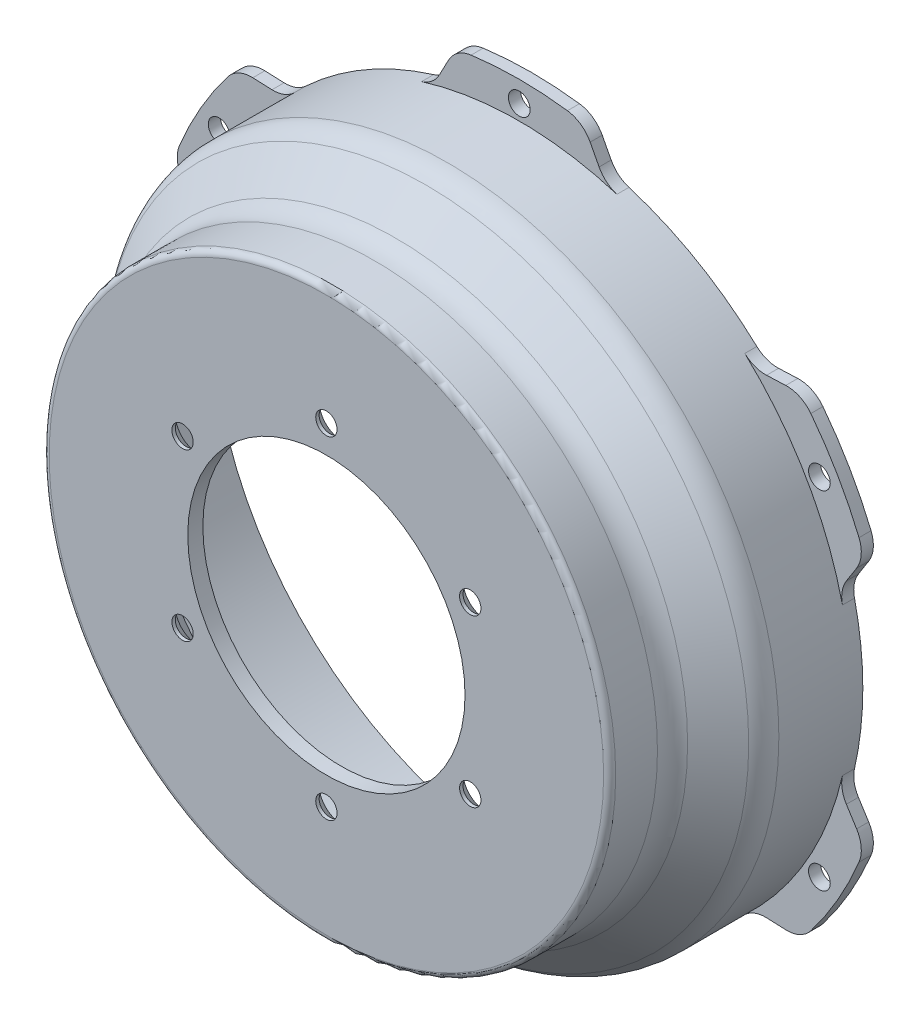
SolidWorks part; units mm, degrees
ref_plane "Front Plane" through (0, 0, 0) normal (0, 0, 1) x (1, 0, 0)
ref_plane "Top Plane" through (0, 0, 0) normal (0, 1, 0) x (1, 0, 0)
ref_plane "Right Plane" through (0, 0, 0) normal (1, 0, 0) x (0, 0, -1)
sketch "Sketch3" plane through (0, 0, 0) normal (1, 0, 0) x (0, 0, -1)
  line L0 (0, 29.21) -> (0, 58.42)
  line L4 (8.4455, 57.15) -> (8.4455, 54.61)
  line L5 (8.4455, 54.61) -> (4.445, 54.61)
  line L6 (3.175, 53.34) -> (3.175, 29.21)
  line L7 (3.175, 29.21) -> (0, 29.21)
  line L8 (0, 0) -> (50000, 0) construction
  line L9 (8.4455, 57.15) -> (14.0335, 57.15)
  line L14 (43.18, 67.31) -> (43.18, 77.47)
  line L15 (14.0335, 57.15) -> (24.1935, 67.31)
  line L16 (24.1935, 67.31) -> (43.18, 67.31)
  line L17 (40.64, 69.85) -> (25.4903, 69.85)
  line L18 (21.0001, 67.9901) -> (14.5599, 61.5499)
  line L19 (10.0697, 59.69) -> (1.27, 59.69)
  line L21 (40.64, 69.85) -> (40.64, 77.47)
  line L22 (40.64, 77.47) -> (43.18, 77.47)
  arc A0 (3.175, 53.34) -> (4.445, 54.61) centre (4.445, 53.34) cw
  arc A5 (0, 58.42) -> (1.27, 59.69) centre (1.27, 58.42) cw
  arc A6 (25.4903, 69.85) -> (21.0001, 67.9901) centre (25.4903, 63.5) ccw
  arc A7 (14.5599, 61.5499) -> (10.0697, 59.69) centre (10.0697, 66.04) cw
  point P32 (12.7, 59.69)
  dimension "D7" = 3.175
  dimension "D10" = 1.27
  dimension "D11" = 12.7
  dimension "D14" = 67.31
  dimension "D4" = 14.0335
  dimension "D2" = 6.35
  dimension "D3" = 29.21
  dimension "D5" = 8.4455
  dimension "D6" = 54.61
  dimension "D8" = 57.15
  dimension "D9" = 59.69
  dimension "D12" = 43.18
  dimension "D13" = 69.85
  dimension "D15" = 45
  dimension "D16" = 40.64
  dimension "D17" = 77.47
revolve "Revolve1" add sketch "Sketch3" angle 360 about L8
sketch "Sketch6" plane through (0, 0, -3.175) normal (0, 0, -1) x (-1, 0, 0)
  point P0 (0, 35)
  dimension "D1" = 35
hole_wizard "CSK for M4 Countersunk Flat Head Screw2" positions "Sketch6" profile "Sketch7" countersink size "M4" standard "ISO"
sketch "Sketch7" plane through (0, 35, -3.175) normal (1, 0, 0) x (0, 1, 0)
  line L0 (0, 0) -> (0, 4.5269)
  line L1 (0, 4.5269) -> (2.25, 3.175)
  line L2 (2.25, 3.175) -> (2.25, 2.45)
  line L3 (2.25, 2.45) -> (4.7, 0)
  line L5 (4.7, 0) -> (0, 0)
  line L6 (-2.25, 2.45) -> (-4.7, 0) construction
  line L10 (0, 4.5269) -> (-2.25, 3.175) construction
  line L11 (0, -6.35) -> (0, 107.95) construction
  dimension "Hole Dia." = 4.5
  dimension "Hole Depth" = 3.175
  dimension "Near C'Sink Dia." = 9.4
  dimension "Near C'Sink Angle" = 90
  dimension "Drill Angle" = 118
pattern_circular "CirPattern2" count 6 over 360 about axis through (0, 0, 0) along (0, 0, 1) of "CSK for M4 Countersunk Flat Head Screw2"
sketch "Sketch8" plane through (0, 0, -40.64) normal (0, 0, 1) x (1, 0, 0)
  line L0 (0, 0) -> (0, 77.47) construction
  line L1 (13.4525, 76.2931) -> (0, 0) construction
  line L2 (18.0785, 67.4699) -> (0, 0) construction
  line L3 (14.9401, 73.4558) -> (16.8195, 69.8713)
  line L4 (0, 0) -> (34.925, 60.4919) construction
  line L5 (-14.9401, 73.4558) -> (-16.8195, 69.8713)
  line L6 (56.1445, 49.6664) -> (52.1005, 49.5017)
  line L7 (71.0846, 23.7894) -> (68.92, 20.3695)
  line L8 (71.0846, -23.7894) -> (68.92, -20.3695)
  line L9 (56.1445, -49.6664) -> (52.1005, -49.5017)
  line L10 (14.9401, -73.4558) -> (16.8195, -69.8713)
  line L11 (-14.9401, -73.4558) -> (-16.8195, -69.8713)
  line L12 (-56.1445, -49.6664) -> (-52.1005, -49.5017)
  line L13 (-71.0846, -23.7894) -> (-68.92, -20.3695)
  line L14 (-71.0846, 23.7894) -> (-68.92, 20.3695)
  line L15 (-56.1445, 49.6664) -> (-52.1005, 49.5017)
  circle A0 centre (0, 0) radius 77.47 construction
  circle A1 centre (0, 0) radius 69.85 construction
  circle A2 centre (0, 0) radius 69.85 construction
  circle A3 centre (0, 0) radius 77.47
  arc A4 (-10.148, 76.8025) -> (10.148, 76.8025) centre (0, 0) cw
  arc A5 (20.5731, 66.7516) -> (34.925, 60.4919) centre (0, 0) cw
  arc A6 (10.148, 76.8025) -> (14.9401, 73.4558) centre (9.3162, 70.5072) cw
  arc A7 (-20.5731, 66.7516) -> (-34.925, 60.4919) centre (0, 0) ccw
  arc A8 (-10.148, 76.8025) -> (-14.9401, 73.4558) centre (-9.3162, 70.5072) ccw
  arc A9 (47.522, 51.1926) -> (34.925, 60.4919) centre (0, 0) ccw
  arc A10 (61.4389, 47.1897) -> (56.1445, 49.6664) centre (56.4029, 43.3217) ccw
  arc A11 (61.4389, 47.1897) -> (71.5869, 29.6128) centre (0, 0) cw
  arc A12 (71.5869, 29.6128) -> (71.0846, 23.7894) centre (65.7191, 27.1855) cw
  arc A13 (68.0951, 15.559) -> (69.85, 0) centre (0, 0) cw
  arc A14 (68.0951, -15.559) -> (69.85, 0) centre (0, 0) ccw
  arc A15 (71.5869, -29.6128) -> (71.0846, -23.7894) centre (65.7191, -27.1855) ccw
  arc A16 (71.5869, -29.6128) -> (61.4389, -47.1897) centre (0, 0) cw
  arc A17 (61.4389, -47.1897) -> (56.1445, -49.6664) centre (56.4029, -43.3217) cw
  arc A18 (47.522, -51.1926) -> (34.925, -60.4919) centre (0, 0) cw
  arc A19 (20.5731, -66.7516) -> (34.925, -60.4919) centre (0, 0) ccw
  arc A20 (10.148, -76.8025) -> (14.9401, -73.4558) centre (9.3162, -70.5072) ccw
  arc A21 (10.148, -76.8025) -> (-10.148, -76.8025) centre (0, 0) cw
  arc A22 (-10.148, -76.8025) -> (-14.9401, -73.4558) centre (-9.3162, -70.5072) cw
  arc A23 (-20.5731, -66.7516) -> (-34.925, -60.4919) centre (0, 0) cw
  arc A24 (-47.522, -51.1926) -> (-34.925, -60.4919) centre (0, 0) ccw
  arc A25 (-61.4389, -47.1897) -> (-56.1445, -49.6664) centre (-56.4029, -43.3217) ccw
  arc A26 (-61.4389, -47.1897) -> (-71.5869, -29.6128) centre (0, 0) cw
  arc A27 (-71.5869, -29.6128) -> (-71.0846, -23.7894) centre (-65.7191, -27.1855) cw
  arc A28 (-68.0951, -15.559) -> (-69.85, 0) centre (0, 0) cw
  arc A29 (-68.0951, 15.559) -> (-69.85, 0) centre (0, 0) ccw
  arc A30 (-71.5869, 29.6128) -> (-71.0846, 23.7894) centre (-65.7191, 27.1855) ccw
  arc A31 (-71.5869, 29.6128) -> (-61.4389, 47.1897) centre (0, 0) cw
  arc A32 (-61.4389, 47.1897) -> (-56.1445, 49.6664) centre (-56.4029, 43.3217) cw
  arc A33 (-47.522, 51.1926) -> (-34.925, 60.4919) centre (0, 0) cw
  arc A34 (-52.1005, 49.5017) -> (-47.522, 51.1926) centre (-51.8422, 55.8465) ccw
  arc A35 (-68.0951, 15.559) -> (-68.92, 20.3695) centre (-74.2856, 16.9734) ccw
  arc A36 (-68.92, -20.3695) -> (-68.0951, -15.559) centre (-74.2856, -16.9734) ccw
  arc A37 (-47.522, -51.1926) -> (-52.1005, -49.5017) centre (-51.8422, -55.8465) ccw
  arc A38 (-16.8195, -69.8713) -> (-20.5731, -66.7516) centre (-22.4434, -72.8199) ccw
  arc A39 (20.5731, -66.7516) -> (16.8195, -69.8713) centre (22.4434, -72.8199) ccw
  arc A40 (52.1005, -49.5017) -> (47.522, -51.1926) centre (51.8422, -55.8465) ccw
  arc A41 (68.0951, -15.559) -> (68.92, -20.3695) centre (74.2856, -16.9734) ccw
  arc A42 (68.92, 20.3695) -> (68.0951, 15.559) centre (74.2856, 16.9734) ccw
  arc A43 (47.522, 51.1926) -> (52.1005, 49.5017) centre (51.8422, 55.8465) ccw
  arc A44 (20.5731, 66.7516) -> (16.8195, 69.8713) centre (22.4434, 72.8199) cw
  arc A45 (-20.5731, 66.7516) -> (-16.8195, 69.8713) centre (-22.4434, 72.8199) ccw
  circle A46 centre (0, 73.025) radius 2.286
  circle A47 centre (63.2415, 36.5125) radius 2.286
  circle A48 centre (63.2415, -36.5125) radius 2.286
  circle A49 centre (0, -73.025) radius 2.286
  circle A50 centre (-63.2415, -36.5125) radius 2.286
  circle A51 centre (-63.2415, 36.5125) radius 2.286
  point P71 (0, 0)
  point P96 (-18.0785, 67.4699)
  point P104 (0, 0)
  circle M60 centre (0, 0) radius 69.85
  circle M61 centre (0, 0) radius 77.47
  dimension "D3" = 6.35
  dimension "D6" = 6.35
  dimension "D7" = 4.572
  dimension "D1" = 10
  dimension "D2" = 15
  dimension "D4" = 30
  dimension "D8" = 73.025
  dimension "D5" = 6
  dimension "D9" = 6
extrude "Cut-Extrude1" cut sketch "Sketch8" against normal through all contours L7 A42 A41 L8 A15 A12 M60 M61 | L9 A40 A39 L10 A20 A17 M60 M61 | L11 A38 A37 L12 A25 A22 M60 M61 | L13 A36 A35 L14 A30 A27 M60 M61 | A45 L5 A8 A3 A32 L15 A34 M60 | A44 A43 L6 A10 A6 L3 M60 M61 | A46 | A47 | A51 | A50 | A48 | A49
